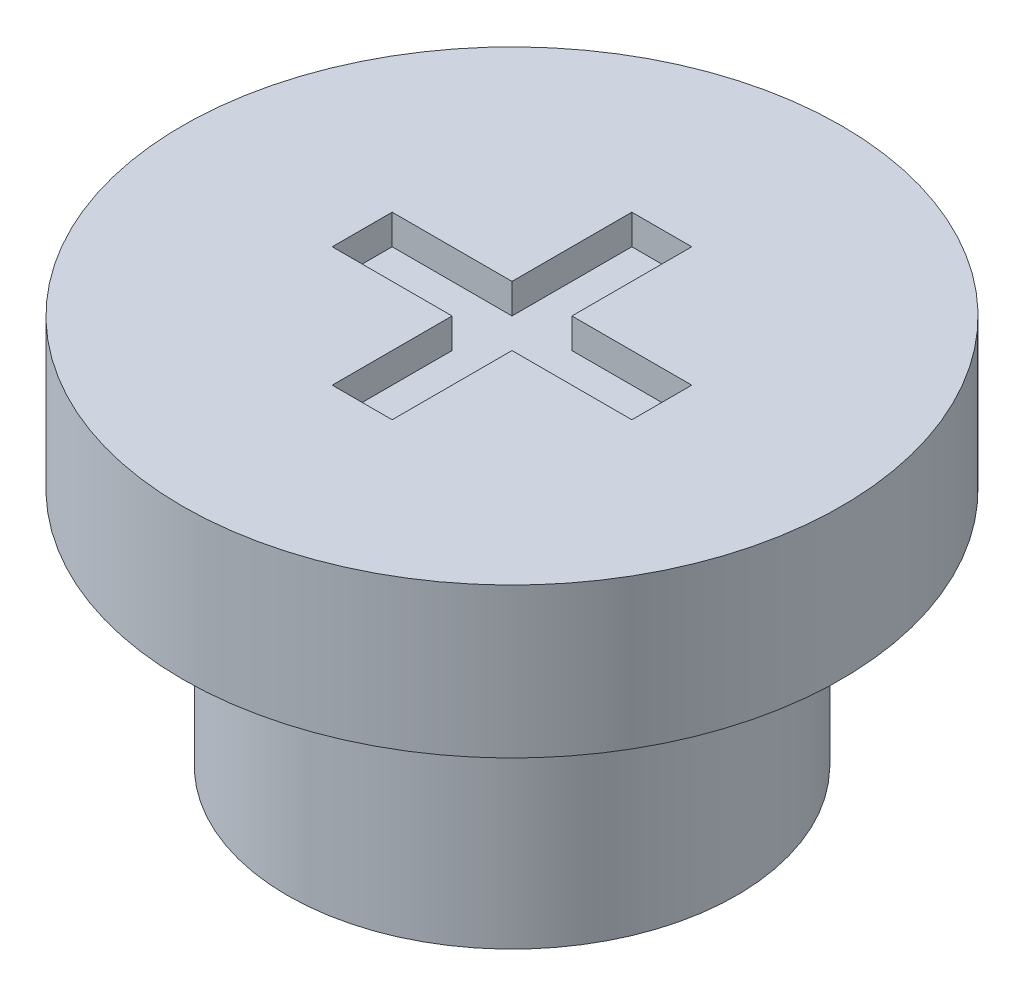
SolidWorks part; units mm, degrees
material "Plain Carbon Steel"
ref_plane "Front Plane" through (0, 0, 0) normal (0, 0, 1) x (1, 0, 0)
ref_plane "Top Plane" through (0, 0, 0) normal (0, 1, 0) x (1, 0, 0)
ref_plane "Right Plane" through (0, 0, 0) normal (1, 0, 0) x (0, 0, -1)
sketch "Sketch1" plane through (0, 0, 0) normal (0, 1, 0) x (1, 0, 0)
  circle A0 centre (0, 0) radius 0.75
  dimension "D1" = 1.5
extrude "Boss-Extrude1" add sketch "Sketch1" along normal blind 0.8
sketch "Sketch2" plane through (0, 0.8, 0) normal (0, 1, 0) x (1, 0, 0)
  circle A0 centre (0, 0) radius 1.1
  dimension "D1" = 2.2
extrude "Boss-Extrude2" add sketch "Sketch2" along normal blind 0.5
sketch "Sketch3" plane through (0, 1.3, 0) normal (0, 1, 0) x (1, 0, 0)
  line L0 (-0.1, -0.1) -> (-0.1, -0.5)
  line L1 (-0.5, 0.1) -> (-0.1, 0.1)
  line L2 (-0.5, 0.1) -> (-0.5, -0.1)
  line L3 (-0.5, -0.1) -> (-0.1, -0.1)
  line L4 (0.5, 0.1) -> (0.5, -0.1)
  line L5 (-0.1, 0.5) -> (0.1, 0.5)
  line L6 (-0.1, 0.5) -> (-0.1, 0.1)
  line L7 (-0.1, -0.5) -> (0.1, -0.5)
  line L8 (0.1, 0.5) -> (0.1, 0.1)
  line L9 (0.1, 0.1) -> (0.5, 0.1)
  line L10 (0.1, -0.1) -> (0.1, -0.5)
  line L11 (0.1, -0.1) -> (0.5, -0.1)
  dimension "D1" = 0.1
  dimension "D2" = 0.1
  dimension "D3" = 0.5
  dimension "D4" = 0.5
  dimension "D5" = 0.1
  dimension "D6" = 0.1
  dimension "D7" = 0.5
  dimension "D8" = 0.5
extrude "Cut-Extrude1" cut sketch "Sketch3" against normal blind 0.1
